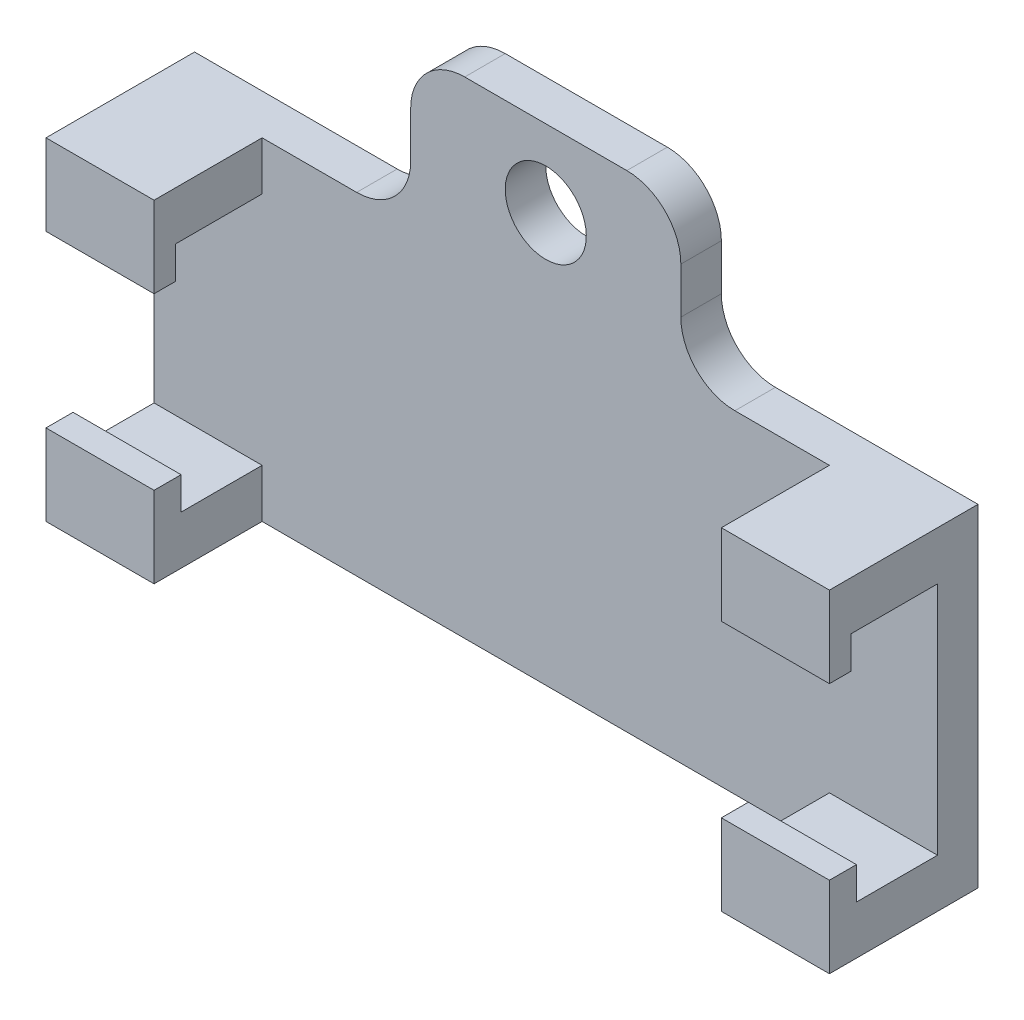
SolidWorks part; units mm, degrees
ref_plane "Front" through (0, 0, 0) normal (0, 0, 1) x (1, 0, 0)
ref_plane "Top" through (0, 0, 0) normal (0, 1, 0) x (1, 0, 0)
ref_plane "Right" through (0, 0, 0) normal (1, 0, 0) x (0, 0, -1)
sketch "Sketch1" plane through (0, 0, 0) normal (0, 1, 0) x (1, 0, 0)
  line L1 (0, 0) -> (29, 0)
  line L2 (0, 0) -> (0, 23.7)
  line L3 (0, 23.7) -> (29, 23.7)
  line L4 (29, 0) -> (29, 23.7)
  dimension "D1" = 29
  dimension "D2" = 23.7
extrude "Boss-Extrude1" add sketch "Sketch1" along normal blind 1.5
sketch "Sketch2" plane through (0, 1.5, 0) normal (0, 1, 0) x (1, 0, 0)
  line L0 (0, 23.7) -> (0, 0) construction
  line L1 (0, 15) -> (29, 15)
  line L2 (0, 15) -> (0, 18)
  line L3 (0, 18) -> (29, 18)
  line L4 (29, 15) -> (29, 18)
  line L5 (29, 0) -> (29, 23.7) construction
  line L7 (0, 8.7) -> (29, 8.7)
  line L8 (0, 8.7) -> (0, 5.7)
  line L9 (0, 5.7) -> (29, 5.7)
  line L10 (29, 8.7) -> (29, 5.7)
  line L11 (14.5, 8.7) -> (14.5, 15) construction
  point P14 (0, 11.85)
  point P15 (14.5, 11.85)
  dimension "D2" = 3
  dimension "D3" = 3
  dimension "D1" = 6.3
extrude "Boss-Extrude2" add sketch "Sketch2" along normal blind 4
sketch "Sketch3" plane through (0, 0, -15) normal (0, 0, 1) x (1, 0, 0)
  line L0 (29, 5.5) -> (29, 1.5) construction
  line L1 (0, 1.5) -> (29, 1.5)
  line L2 (0, 1.5) -> (0, 4.7)
  line L3 (0, 4.7) -> (29, 4.7)
  line L4 (29, 1.5) -> (29, 4.7)
  dimension "D1" = 3.2
extrude "Cut-Extrude1" cut sketch "Sketch3" against normal blind 1.2
sketch "Sketch4" plane through (0, 0, -8.7) normal (0, 0, -1) x (-1, 0, 0)
  line L0 (0, 5.5) -> (0, 1.5) construction
  line L1 (-29, 1.5) -> (0, 1.5)
  line L2 (-29, 1.5) -> (-29, 4.5)
  line L3 (-29, 4.5) -> (0, 4.5)
  line L4 (0, 1.5) -> (0, 4.5)
  dimension "D1" = 3
extrude "Cut-Extrude2" cut sketch "Sketch4" against normal blind 1.2
sketch "Sketch5" plane through (0, 1.5, 0) normal (0, 1, 0) x (1, 0, 0)
  line L0 (0, 23.7) -> (0, 18) construction
  line L1 (29, 23.7) -> (0, 23.7) construction
  line L2 (0, 5.7) -> (0, 0) construction
  circle A0 centre (14.5, 20.85) radius 1.5
  circle A1 centre (14.5, 2.85) radius 1.5
  point P6 (0, 20.85)
  point P9 (14.5, 23.7)
  point P12 (0, 2.85)
  dimension "D1" = 3
  dimension "D2" = 3
extrude "Cut-Extrude3" cut sketch "Sketch5" against normal through all
sketch "Sketch6" plane through (0, 0, 0) normal (0, -1, 0) x (1, 0, 0)
  line L0 (14.5, -20.85) -> (14.5, -5.7)
  line L1 (0, -5.7) -> (29, -5.7) construction
sketch "Sketch7" plane through (0, 0, 0) normal (0, 1, 0) x (1, 0, 0)
  line L1 (0, 5.7) -> (29, 5.7)
  line L2 (0, 5.7) -> (0, 0)
  line L3 (0, 0) -> (29, 0)
  line L4 (29, 5.7) -> (29, 0)
extrude "Cut-Extrude4" cut sketch "Sketch7" along normal through all
sketch "Sketch8" plane through (0, 0, -5.7) normal (0, 0, 1) x (1, 0, 0)
  line L0 (0, 5.5) -> (29, 5.5) construction
  line L1 (4, 5.5) -> (25, 5.5)
  line L2 (4, 5.5) -> (4, 1.5)
  line L3 (4, 1.5) -> (25, 1.5)
  line L4 (25, 5.5) -> (25, 1.5)
  line L5 (0, 1.5) -> (29, 1.5) construction
  line L6 (0, 1.5) -> (4, 1.5) construction
  line L16 (0, 5.5) -> (0, 0) construction
  point P8 (14.5, 5.5)
  point P9 (14.5, 5.5)
  dimension "D1" = 4
extrude "Cut-Extrude5" cut sketch "Sketch8" against normal through all
sketch "Sketch9" plane through (0, 1.5, 0) normal (0, 1, 0) x (1, 0, 0)
  line L0 (4, 18) -> (0, 18) construction
  line L1 (0, 23.7) -> (9.5, 23.7)
  line L2 (0, 23.7) -> (0, 18)
  line L3 (0, 18) -> (9.5, 18)
  line L4 (9.5, 23.7) -> (9.5, 18)
  line L5 (14.5, 23.7) -> (14.5, 5.7) construction
  line L6 (29, 23.7) -> (0, 23.7) construction
  line L7 (4, 5.7) -> (25, 5.7) construction
  line L8 (19.5, 23.7) -> (19.5, 18)
  line L9 (29, 18) -> (19.5, 18)
  line L10 (29, 23.7) -> (29, 18)
  line L11 (29, 23.7) -> (19.5, 23.7)
  dimension "D1" = 5
extrude "Cut-Extrude6" cut sketch "Sketch9" against normal through all
fillet "Fillet1" radius 2 4 edges at (9.5, 0.75, -18) (9.5, 0.75, -23.7) (19.5, 0.75, -23.7) (19.5, 0.75, -18)
move or copy body "Body-Move/Copy1" bodies to move or copy 109 copy no rotation origin (0, 2.75, -20.7) rotation axis (1, 0, 0) rotation angle 90
equation "\"Board Length\"= 8.7'The dimension of the board parallel with the clips"
equation "\"Board Width\"= 29'The dimension of the board perpendicular to the clips"
equation "\"D1@Sketch1\"=\"Board Width\""
equation "\"Board Slot Length\"= \"Board Length\" - 2 * \"Overhang Cut\""
equation "\"Overhang Cut\"= 1.2"
equation "\"D1@Cut-Extrude1\"=\"Overhang Cut\""
equation "\"D1@Sketch2\"=\"Board Slot Length\""
equation "\"Mount Length\"= \"Board Length\" + 7.5 * 2"
equation "\"D2@Sketch1\"=\"Mount Length\""
